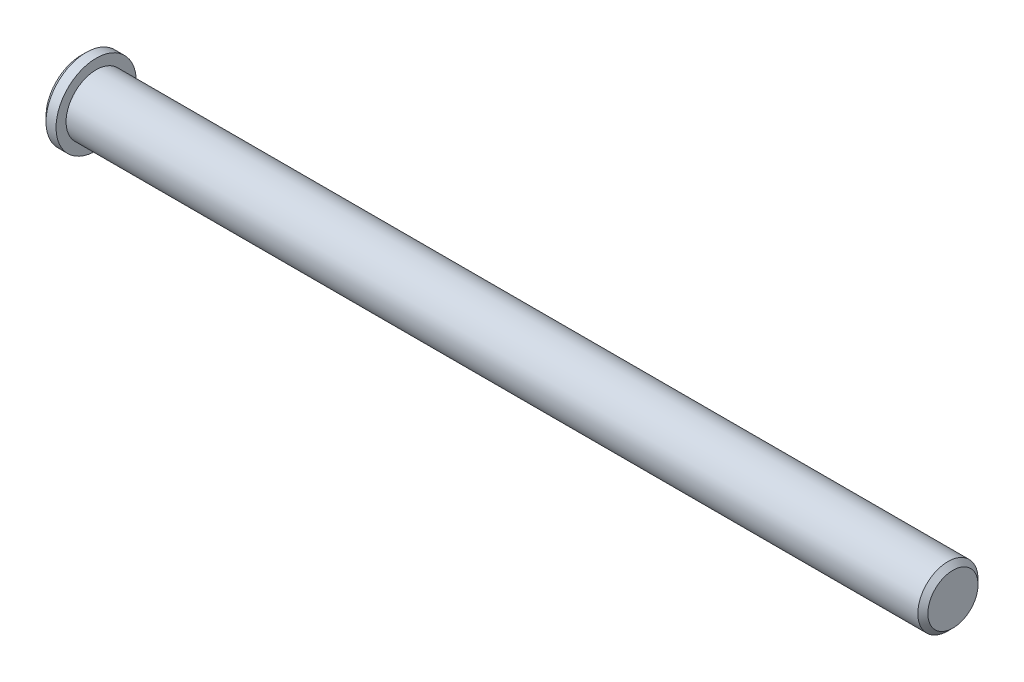
SolidWorks part; units mm, degrees
material "Alloy Steel"
ref_plane "Front Plane" through (0, 0, 0) normal (0, 0, 1) x (1, 0, 0)
ref_plane "Top Plane" through (0, 0, 0) normal (0, 1, 0) x (1, 0, 0)
ref_plane "Right Plane" through (0, 0, 0) normal (1, 0, 0) x (0, 0, -1)
sketch "Sketch1" plane through (0, 0, 0) normal (0, 0, 1) x (1, 0, 0)
  line L0 (0, 0) -> (0, 8)
  line L1 (3, 6) -> (173.8, 6)
  line L2 (173.8, 6) -> (173.8, 0)
  line L3 (173.8, 0) -> (0, 0)
  line L4 (3, 6) -> (3, 8)
  line L5 (3, 8) -> (0, 8)
  dimension "D1" = 170.8
  dimension "D2" = 6
  dimension "D3" = 8
  dimension "D4" = 3
revolve "Revolve1" add sketch "Sketch1" angle 360 about L3
cosmetic thread "Cosmetic Thread1" parameters "D1"=13, "D2"=10.344
sketch "Sketch2" plane through (0, 0, 0) normal (-1, 0, 0) x (0, 0, 1)
  line L1 (0, 5) -> (-4.3301, 2.5)
  line L2 (-4.3301, 2.5) -> (-4.3301, -2.5)
  line L3 (-4.3301, -2.5) -> (0, -5)
  line L4 (0, -5) -> (4.3301, -2.5)
  line L5 (4.3301, -2.5) -> (4.3301, 2.5)
  line L6 (4.3301, 2.5) -> (0, 5)
  circle A0 centre (0, 0) radius 4.3301 construction
  dimension "D1" = 5
extrude "Cut-Extrude1" cut sketch "Sketch2" against normal blind 4
chamfer "Chamfer1" distance 1 angle 45 2 edges at (0, 8, 0) (173.8, 6, 0)
